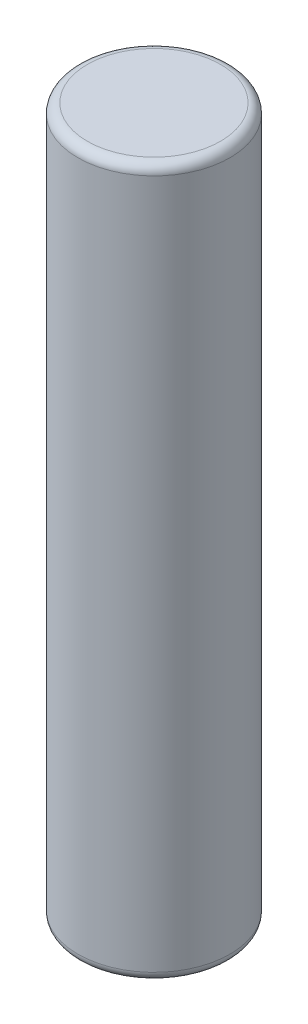
SolidWorks part; units mm, degrees
ref_plane "Front Plane" through (0, 0, 0) normal (0, 0, 1) x (1, 0, 0)
ref_plane "Top Plane" through (0, 0, 0) normal (0, 1, 0) x (1, 0, 0)
ref_plane "Right Plane" through (0, 0, 0) normal (1, 0, 0) x (0, 0, -1)
sketch "Sketch1" plane through (0, 0, 0) normal (0, 1, 0) x (1, 0, 0)
  circle A0 centre (0, 0) radius 4
  dimension "D1" = 8
extrude "Boss-Extrude1" add sketch "Sketch1" along normal blind 37.25
fillet "Fillet1" radius 0.5 2 edges at (0, 0, 4) (0, 37.25, 4)
